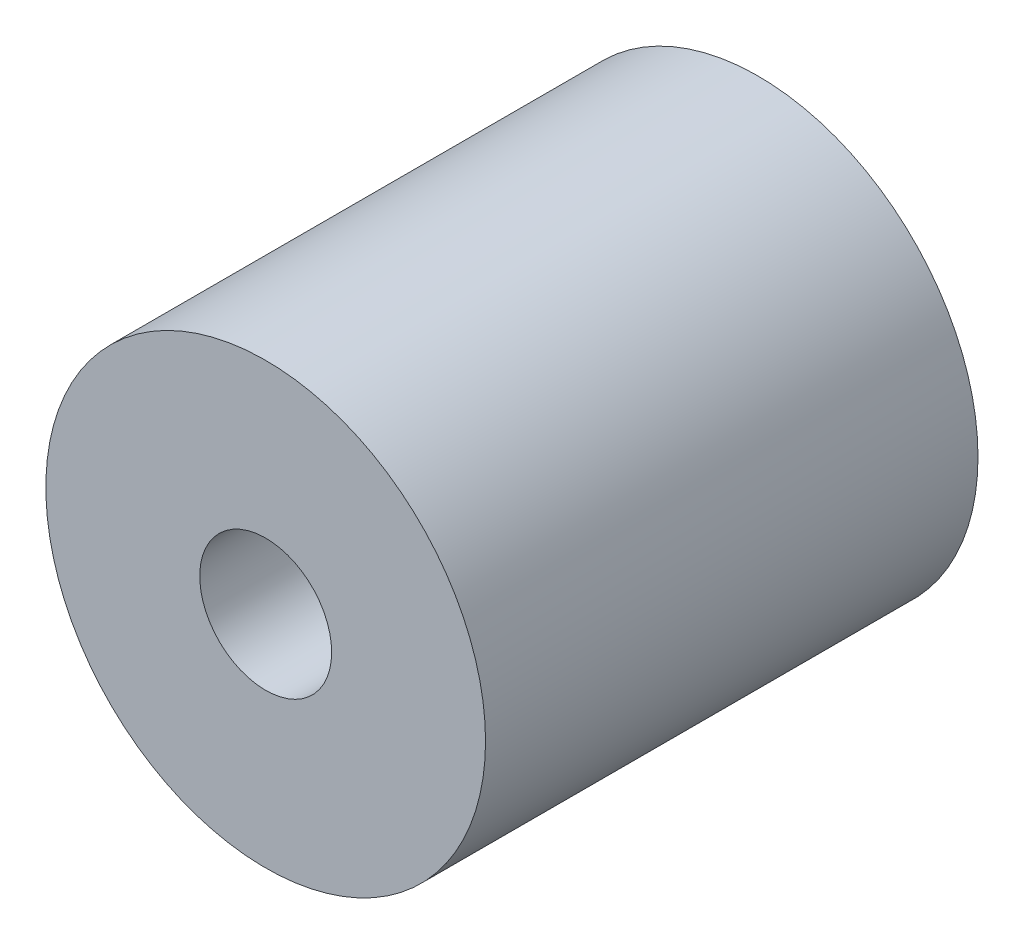
SolidWorks part; units mm, degrees
ref_plane "Front Plane" through (0, 0, 0) normal (0, 0, 1) x (1, 0, 0)
ref_plane "Top Plane" through (0, 0, 0) normal (0, 1, 0) x (1, 0, 0)
ref_plane "Right Plane" through (0, 0, 0) normal (1, 0, 0) x (0, 0, -1)
sketch "Sketch1" plane through (0, 0, 0) normal (0, 0, 1) x (1, 0, 0)
  circle A0 centre (0, 0) radius 7.9375
  circle A1 centre (0, 0) radius 2.3813
  dimension "D1" = 4.7625
  dimension "D2" = 15.875
extrude "Boss-Extrude1" add sketch "Sketch1" along normal blind 17.78
